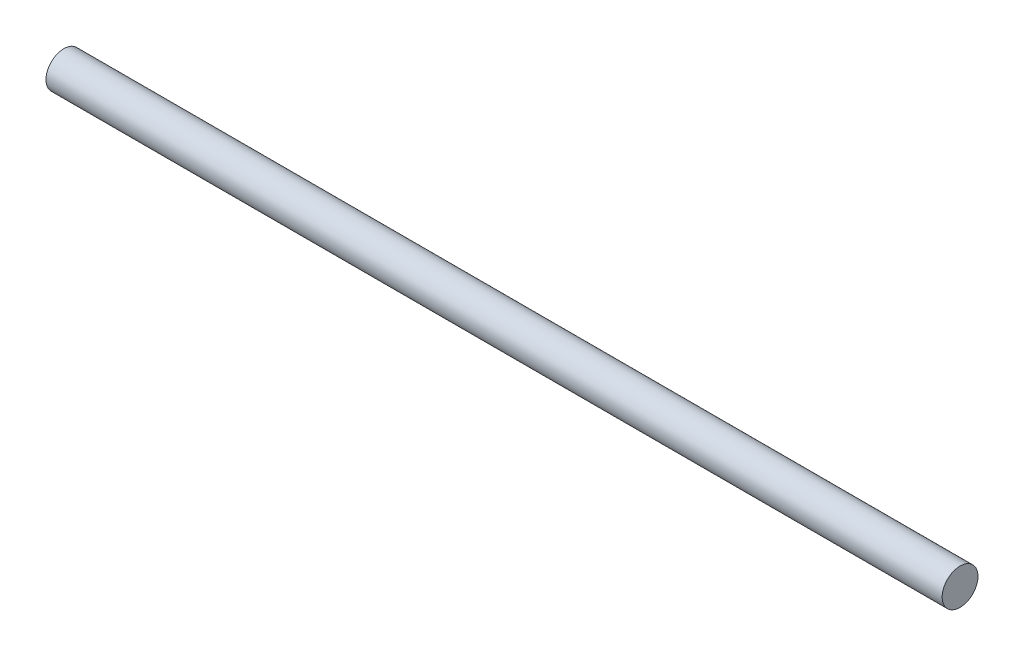
SolidWorks part; units mm, degrees
ref_plane "前视基准面" through (0, 0, 0) normal (0, 0, 1) x (1, 0, 0)
ref_plane "上视基准面" through (0, 0, 0) normal (0, 1, 0) x (1, 0, 0)
ref_plane "右视基准面" through (0, 0, 0) normal (1, 0, 0) x (0, 0, -1)
sketch "草图1" plane through (0, 0, 0) normal (1, 0, 0) x (0, 0, -1)
  circle A0 centre (0, 0) radius 4
extrude "凸台-拉伸1" add sketch "草图1" along normal blind 200
